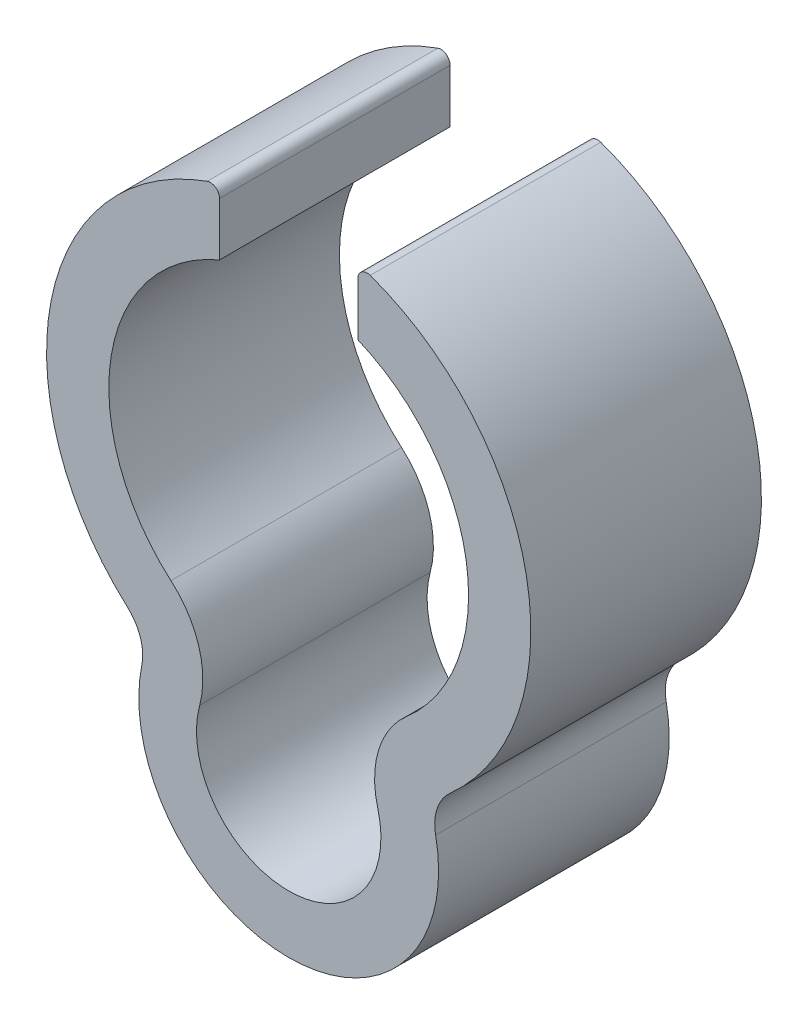
SolidWorks part; units mm, degrees
ref_plane "Přední rovina" through (0, 0, 0) normal (0, 0, 1) x (1, 0, 0)
ref_plane "Horní rovina" through (0, 0, 0) normal (0, 1, 0) x (1, 0, 0)
ref_plane "Pravá rovina" through (0, 0, 0) normal (1, 0, 0) x (0, 0, -1)
sketch "Skica1" plane through (0, 0, 0) normal (0, 0, 1) x (1, 0, 0)
  line L0 (0, 0) -> (0, -5.5) construction
  line L1 (-1.5, 5.0312) -> (-1.5, 3.6)
  line L2 (-1.5, 0) -> (0, 0)
  line L3 (0, 0) -> (1.5, 0)
  line L4 (1.5, 3.6) -> (1.5, 5.0312)
  line L5 (1.5, 0) -> (1.5, 3.6)
  line L6 (-1.5, 0) -> (-1.5, 3.6)
  arc A0 (-1.5, 3.6) -> (-2.5531, -2.9481) centre (0, 0) ccw
  arc A1 (-1.5, 5.0312) -> (-3.4994, -3.9136) centre (0, 0) ccw
  arc A4 (-1.9312, -4.98) -> (1.9312, -4.98) centre (0, -5.5) ccw
  arc A5 (-3.1857, -4.857) -> (3.1857, -4.857) centre (0, -5.5) ccw
  arc A6 (2.5531, -2.9481) -> (1.5, 3.6) centre (0, 0) ccw
  arc A7 (3.4994, -3.9136) -> (1.5, 5.0312) centre (0, 0) ccw
  arc A8 (3.4994, -3.9136) -> (3.1857, -4.857) centre (4.166, -4.6591) ccw
  arc A9 (-3.4994, -3.9136) -> (-3.1857, -4.857) centre (-4.166, -4.6591) cw
  arc A10 (2.5531, -2.9481) -> (1.9312, -4.98) centre (3.8624, -4.46) ccw
  arc A11 (-1.9312, -4.98) -> (-2.5531, -2.9481) centre (-3.8624, -4.46) ccw
  point P19 (1.002, -3.7691)
  dimension "D1" = 7.8
  dimension "D2" = 10.5
  dimension "D3" = 4
  dimension "D4" = 5.5
  dimension "D5" = 6.5
  dimension "D8" = 1
  dimension "D9" = 2
  dimension "D6" = 1.5
  dimension "D7" = 1.5
extrude "Přidat vysunutím1" add sketch "Skica1" along normal blind 5 contours A4 A11 A0 L1 A1 A9 A5 A8 A7 L4 A6 A10
fillet "Zaoblit1" radius 0.2 2 edges at (1.5, 5.0312, 2.5) (-1.5, 5.0312, 2.5)
